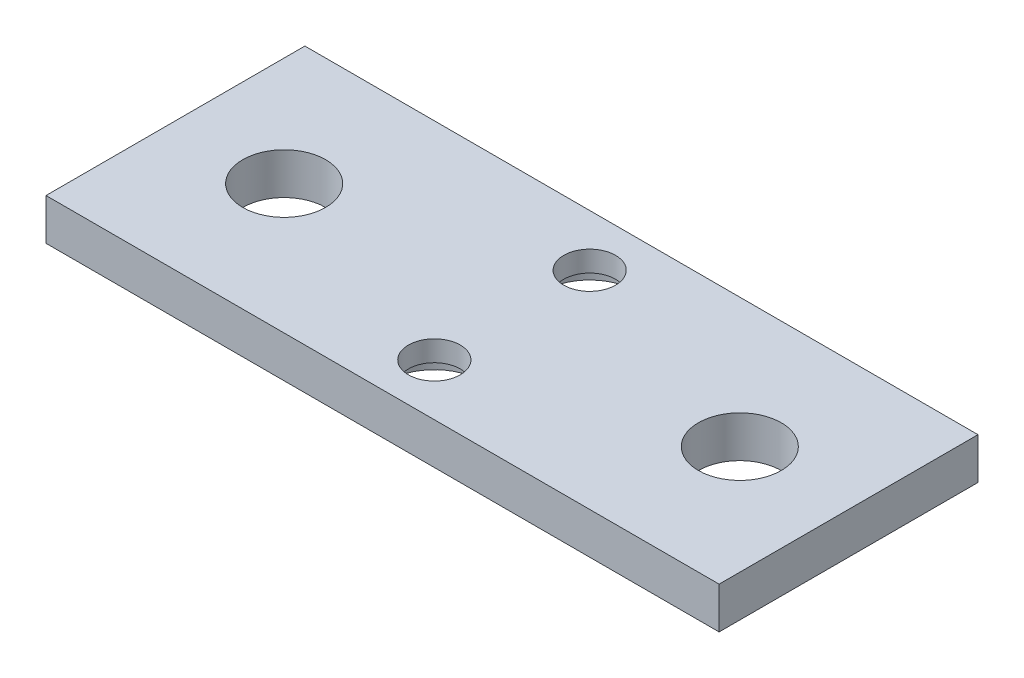
SolidWorks part; units mm, degrees
ref_plane "前视基准面" through (0, 0, 0) normal (0, 0, 1) x (1, 0, 0)
ref_plane "上视基准面" through (0, 0, 0) normal (0, 1, 0) x (1, 0, 0)
ref_plane "右视基准面" through (0, 0, 0) normal (1, 0, 0) x (0, 0, -1)
other "Configuration Table"
sketch "草图1" plane through (0, 0, 0) normal (0, 1, 0) x (1, 0, 0)
  line L1 (-32.5, 12.5) -> (32.5, 12.5)
  line L2 (-32.5, 12.5) -> (-32.5, -12.5)
  line L3 (-32.5, -12.5) -> (32.5, -12.5)
  line L4 (32.5, 12.5) -> (32.5, -12.5)
  line L5 (0, -12.5) -> (0, 12.5) construction
  line L6 (-32.5, 0) -> (32.5, 0) construction
  point P0 (0, 0)
  dimension "D1" = 25
  dimension "D2" = 65
extrude "凸台-拉伸1" add sketch "草图1" along normal blind 4
sketch "草图2" plane through (0, 4, 0) normal (0, 1, 0) x (1, 0, 0)
  line L0 (-32.5, -12.5) -> (32.5, -12.5) construction
  line L1 (-7.5, 12.5) -> (7.5, 12.5)
  line L2 (-7.5, 12.5) -> (-7.5, -12.5)
  line L3 (-7.5, -12.5) -> (7.5, -12.5)
  line L4 (7.5, 12.5) -> (7.5, -12.5)
  line L5 (0, -12.5) -> (0, 12.5) construction
  line L6 (-7.5, 0) -> (7.5, 0) construction
  point P0 (0, 0)
  dimension "D1" = 15
extrude "凸台-拉伸2" add sketch "草图2" along normal blind 13
sketch "草图3" plane through (0, 0, 0) normal (0, -1, 0) x (1, 0, 0)
  line L0 (0, 12.5) -> (0, -12.5) construction
  line L1 (-32.5, 12.5) -> (32.5, 12.5) construction
  line L2 (32.5, -12.5) -> (-32.5, -12.5) construction
  line L3 (-32.5, 0) -> (32.5, 0) construction
  line L4 (-32.5, -12.5) -> (-32.5, 12.5) construction
  line L5 (32.5, 12.5) -> (32.5, -12.5) construction
  circle A0 centre (0, -7.5) radius 2.5
  circle A1 centre (0, 7.5) radius 2.5
  circle A2 centre (-22, 0) radius 4
  circle A3 centre (22, 0) radius 4
  dimension "D1" = 5
  dimension "D3" = 8
  dimension "D2" = 5
  dimension "D4" = 22
extrude "切除-拉伸1" cut sketch "草图3" against normal through all
sketch "草图4" plane through (0, 0, 0) normal (0, -1, 0) x (1, 0, 0)
  circle A0 centre (0, -7.5) radius 4.5
  circle A1 centre (0, 7.5) radius 4.5
  dimension "D1" = 9
extrude "切除-拉伸2" cut sketch "草图4" against normal blind 2
sketch "草图5" plane through (0, 0, 12.5) normal (0, 0, 1) x (1, 0, 0)
  line L0 (7.5, 17) -> (7.5, 4) construction
  line L1 (-7.5, 4) -> (7.5, 4)
  line L2 (-7.5, 4) -> (-7.5, 8)
  line L3 (-7.5, 8) -> (7.5, 8)
  line L4 (7.5, 4) -> (7.5, 8)
  dimension "D1" = 4
extrude "凸台-拉伸3" add sketch "草图5" along normal blind 6
sketch "草图6" plane through (0, 4, 0) normal (0, -1, 0) x (1, 0, 0)
  line L0 (0, 18.5) -> (0, 12.5) construction
  line L1 (-7.5, 18.5) -> (7.5, 18.5) construction
  line L2 (-32.5, 12.5) -> (32.5, 12.5) construction
  line L3 (-7.5, 18.5) -> (-7.5, 12.5) construction
  circle A0 centre (-4.5, 15.5) radius 1.25
  circle A1 centre (4.5, 15.5) radius 1.25
  point P11 (-7.5, 15.5)
  dimension "D1" = 2.5
  dimension "D2" = 3
extrude "切除-拉伸3" cut sketch "草图6" against normal through all
ref_plane "基准面2" through (0, 0, 0) normal (0, 0, 1) x (1, 0, 0)
mirror "镜向2" about plane through (0, 0, 0) normal (0, 0, 1) of "凸台-拉伸3", "切除-拉伸3"
fillet "圆角2" radius 3 4 edges at (-7.5, 6, -18.5) (7.5, 6, -18.5) (-7.5, 6, 18.5) (7.5, 6, 18.5)
sketch "草图9" plane through (0, 0, 18.5) normal (0, 0, 1) x (1, 0, 0)
  line L1 (-7.5, 17) -> (7.5, 17)
  line L2 (-7.5, 17) -> (-7.5, 4)
  line L3 (-7.5, 4) -> (7.5, 4)
  line L4 (7.5, 17) -> (7.5, 4)
extrude "切除-拉伸4" cut sketch "草图9" against normal through all
